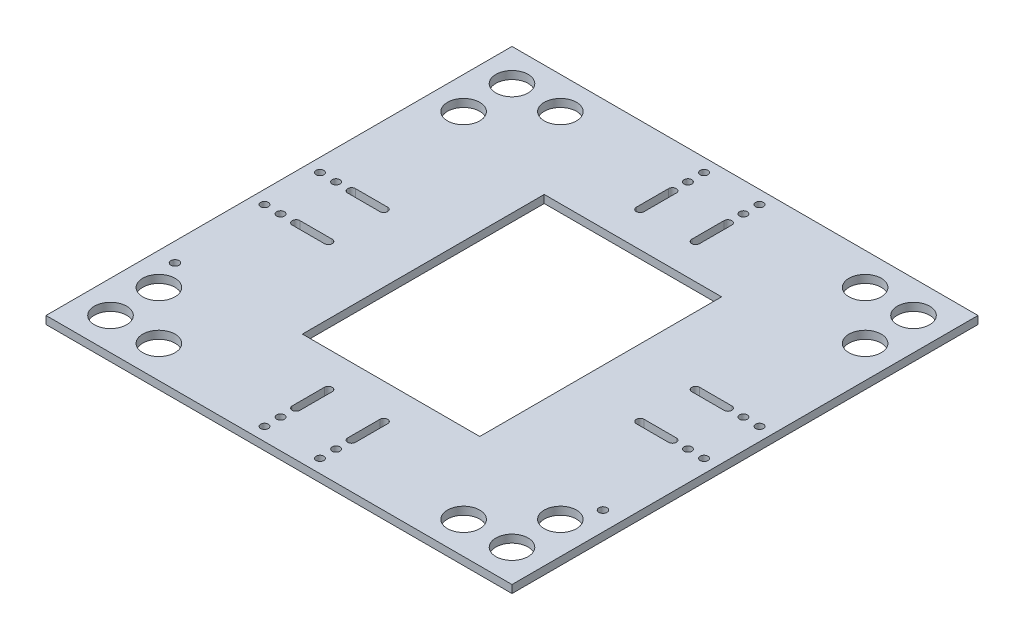
SolidWorks part; units mm, degrees
material "Acrylic (Medium-high impact)"
ref_plane "Front Plane" through (0, 0, 0) normal (0, 0, 1) x (1, 0, 0)
ref_plane "Top Plane" through (0, 0, 0) normal (0, 1, 0) x (1, 0, 0)
ref_plane "Right Plane" through (0, 0, 0) normal (1, 0, 0) x (0, 0, -1)
sketch "Sketch3" plane through (0, 0, 0) normal (0, 1, 0) x (1, 0, 0)
  line L1 (0, 0) -> (183.52, 0)
  line L2 (0, 0) -> (0, 183.52)
  line L3 (0, 183.52) -> (183.52, 183.52)
  line L4 (183.52, 0) -> (183.52, 183.52)
  dimension "D1" = 183.52
  dimension "D2" = 183.52
extrude "Boss-Extrude1" add sketch "Sketch3" along normal blind 3.0988
sketch "Sketch4" plane through (0, 3.0988, 0) normal (0, 1, 0) x (1, 0, 0)
  line L0 (0, 91.76) -> (183.52, 91.76) construction
  line L1 (0, 183.52) -> (0, 0) construction
  line L2 (183.52, 0) -> (183.52, 183.52) construction
  line L3 (91.76, 183.52) -> (91.76, 0) construction
  line L4 (-1025.7031, 102.682) -> (48974.2969, 102.682) construction
  line L5 (17.646, 101.158) -> (30.346, 101.158)
  line L6 (17.646, 104.206) -> (30.346, 104.206)
  line L7 (183.52, 183.52) -> (0, 183.52) construction
  line L8 (0, 0) -> (183.52, 0) construction
  line L9 (-1025.7031, 80.838) -> (48974.2969, 80.838) construction
  line L10 (17.646, 79.314) -> (30.346, 79.314)
  line L11 (17.646, 82.362) -> (30.346, 82.362)
  line L12 (1240.6011, 80.838) -> (-48759.3989, 80.838) construction
  line L13 (1209.2232, 102.682) -> (-48790.7768, 102.682) construction
  line L14 (165.874, 82.362) -> (153.174, 82.362)
  line L15 (165.874, 79.314) -> (153.174, 79.314)
  line L16 (165.874, 104.206) -> (153.174, 104.206)
  line L17 (165.874, 101.158) -> (153.174, 101.158)
  line L18 (80.838, -759.6953) -> (80.838, 49240.3047) construction
  line L19 (79.314, 153.167) -> (79.314, 165.867)
  line L20 (82.362, 153.167) -> (82.362, 165.867)
  line L21 (102.682, -759.6953) -> (102.682, 49240.3047) construction
  line L22 (101.158, 153.167) -> (101.158, 165.867)
  line L23 (104.206, 153.167) -> (104.206, 165.867)
  line L24 (104.206, 30.353) -> (104.206, 17.653)
  line L25 (101.158, 30.353) -> (101.158, 17.653)
  line L26 (82.362, 30.353) -> (82.362, 17.653)
  line L27 (79.314, 30.353) -> (79.314, 17.653)
  circle A0 centre (5.2, 102.682) radius 1.524
  arc A1 (17.646, 104.206) -> (17.646, 101.158) centre (17.646, 102.682) ccw
  circle A2 centre (11.55, 102.682) radius 1.524
  arc A3 (30.346, 101.158) -> (30.346, 104.206) centre (30.346, 102.682) ccw
  arc A4 (30.346, 82.362) -> (30.346, 79.314) centre (30.346, 80.838) cw
  circle A5 centre (11.55, 80.838) radius 1.524
  arc A6 (17.646, 79.314) -> (17.646, 82.362) centre (17.646, 80.838) cw
  circle A7 centre (5.2, 80.838) radius 1.524
  circle A8 centre (178.32, 80.838) radius 1.524
  arc A9 (165.874, 79.314) -> (165.874, 82.362) centre (165.874, 80.838) ccw
  circle A10 centre (171.97, 80.838) radius 1.524
  arc A11 (153.174, 82.362) -> (153.174, 79.314) centre (153.174, 80.838) ccw
  arc A12 (153.174, 101.158) -> (153.174, 104.206) centre (153.174, 102.682) cw
  circle A13 centre (171.97, 102.682) radius 1.524
  arc A14 (165.874, 104.206) -> (165.874, 101.158) centre (165.874, 102.682) cw
  circle A15 centre (178.32, 102.682) radius 1.524
  circle A16 centre (80.838, 178.313) radius 1.524
  circle A17 centre (80.838, 171.963) radius 1.524
  arc A18 (82.362, 165.867) -> (79.314, 165.867) centre (80.838, 165.867) ccw
  arc A19 (79.314, 153.167) -> (82.362, 153.167) centre (80.838, 153.167) ccw
  arc A20 (104.206, 153.167) -> (101.158, 153.167) centre (102.682, 153.167) cw
  arc A21 (101.158, 165.867) -> (104.206, 165.867) centre (102.682, 165.867) cw
  circle A22 centre (102.682, 171.963) radius 1.524
  circle A23 centre (102.682, 178.313) radius 1.524
  circle A24 centre (102.682, 5.207) radius 1.524
  circle A25 centre (102.682, 11.557) radius 1.524
  arc A26 (101.158, 17.653) -> (104.206, 17.653) centre (102.682, 17.653) ccw
  arc A27 (104.206, 30.353) -> (101.158, 30.353) centre (102.682, 30.353) ccw
  arc A28 (79.314, 30.353) -> (82.362, 30.353) centre (80.838, 30.353) cw
  arc A29 (82.362, 17.653) -> (79.314, 17.653) centre (80.838, 17.653) cw
  circle A30 centre (80.838, 11.557) radius 1.524
  circle A31 centre (80.838, 5.207) radius 1.524
  dimension "D1" = 3.048
  dimension "D2" = 6.35
  dimension "D3" = 6.096
  dimension "D4" = 12.7
  dimension "D9" = 6.096
  dimension "D10" = 5.207
  dimension "D11" = 12.7
  dimension "D12" = 79.314
  dimension "D7" = 3.048
  dimension "D5" = 5.2
  dimension "D6" = 79.314
  dimension "D8" = 6.35
extrude "Cut-Extrude1" cut sketch "Sketch4" against normal through all
sketch "Sketch5" plane through (0, 3.0988, 0) normal (0, 1, 0) x (1, 0, 0)
  line L0 (0, 91.76) -> (183.52, 91.76) construction
  line L1 (56.835, 139.385) -> (126.685, 139.385)
  line L2 (56.835, 139.385) -> (56.835, 44.135)
  line L3 (56.835, 44.135) -> (126.685, 44.135)
  line L4 (126.685, 139.385) -> (126.685, 44.135)
  line L5 (183.52, 183.52) -> (0, 183.52) construction
  line L6 (0, 183.52) -> (0, 0) construction
  line L7 (183.52, 0) -> (183.52, 183.52) construction
  line L9 (0, 0) -> (183.52, 0) construction
  line L13 (91.76, 183.52) -> (91.76, 0) construction
  circle A0 centre (170.82, 151.77) radius 6.35
  circle A1 centre (170.82, 170.82) radius 6.35
  circle A2 centre (151.77, 170.82) radius 6.35
  circle A3 centre (170.82, 31.75) radius 6.35
  circle A4 centre (12.7, 31.75) radius 6.35
  circle A5 centre (12.7, 12.7) radius 6.35
  circle A6 centre (31.75, 12.7) radius 6.35
  circle A7 centre (151.77, 12.7) radius 6.35
  circle A8 centre (31.75, 170.82) radius 6.35
  circle A9 centre (12.7, 170.82) radius 6.35
  circle A10 centre (12.7, 151.77) radius 6.35
  circle A11 centre (170.82, 12.7) radius 6.35
  point P12 (56.835, 91.76)
  point P26 (91.76, 139.385)
  dimension "D5" = 12.7
  dimension "D6" = 12.7
  dimension "D7" = 12.7
  dimension "D3" = 12.7
  dimension "D1" = 69.85
  dimension "D2" = 95.25
  dimension "D4" = 12.7
  dimension "D8" = 31.75
  dimension "D9" = 31.75
extrude "Cut-Extrude2" cut sketch "Sketch5" against normal up to next
sketch "Sketch7" plane through (0, 3.0988, 0) normal (0, 1, 0) x (1, 0, 0)
  line L0 (7.4828, 43.312) -> (176.0372, 43.312) construction
  line L1 (91.76, 183.52) -> (91.76, 0) construction
  line L2 (183.52, 183.52) -> (0, 183.52) construction
  line L3 (0, 0) -> (183.52, 0) construction
  circle A0 centre (7.4828, 43.312) radius 1.6002
  circle A1 centre (176.0372, 43.312) radius 1.6002
  point P10 (91.76, 43.312)
  dimension "D2" = 3.2004
  dimension "D1" = 168.5544
  dimension "D3" = 140.208
extrude "Cut-Extrude6" cut sketch "Sketch7" against normal blind 2.54
